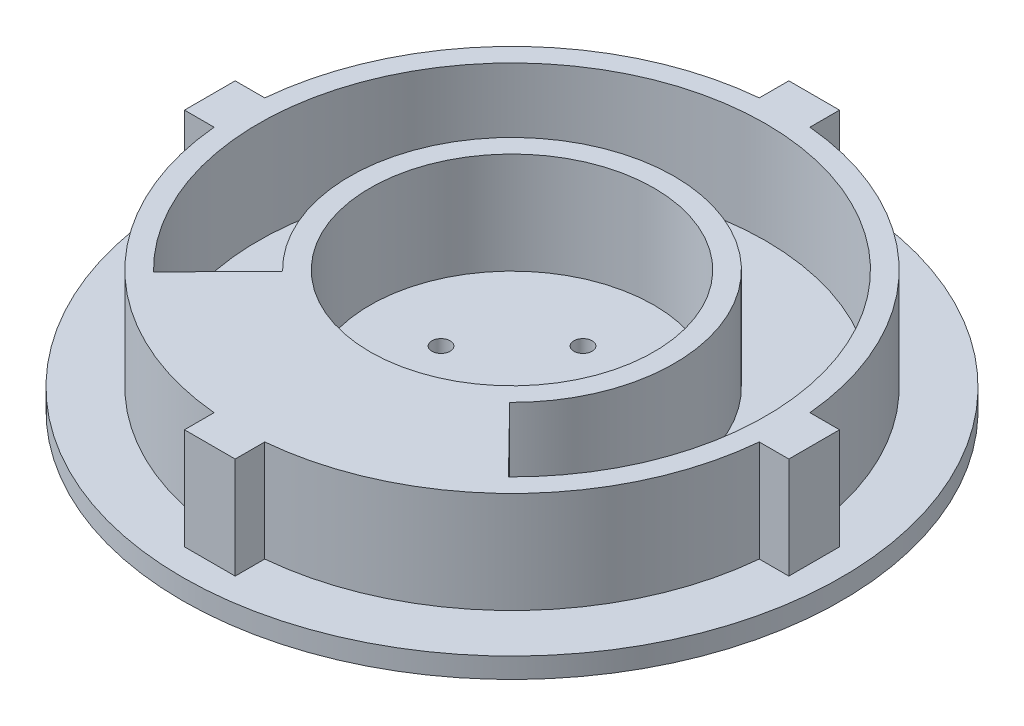
SolidWorks part; units mm, degrees
ref_plane "Front Plane" through (0, 0, 0) normal (0, 0, 1) x (1, 0, 0)
ref_plane "Top Plane" through (0, 0, 0) normal (0, 1, 0) x (1, 0, 0)
ref_plane "Right Plane" through (0, 0, 0) normal (1, 0, 0) x (0, 0, -1)
sketch "Sketch1" plane through (0, 0, 0) normal (0, 1, 0) x (1, 0, 0)
  line L0 (-17.5, -17.8536) -> (-11.2, -11.4263)
  line L1 (0, -55) -> (0, 55) construction
  line L2 (17.5, -17.8536) -> (11.2, -11.4263)
  line L4 (-17.5, -17.8536) -> (3.8221, -38.7535) construction
  circle A0 centre (0, 0) radius 27
  arc A1 (11.2, -11.4263) -> (-11.2, -11.4263) centre (0, 0) ccw
  arc A2 (17.5, -17.8536) -> (-17.5, -17.8536) centre (0, 0) ccw
  circle A3 centre (0, 0) radius 14
  arc A4 (16.5039, 11.7639) -> (14.35, -14.6399) centre (0.1913, -0.1952) cw construction
  circle A5 centre (0, 0) radius 19.9533 construction
  dimension "D1" = 54
  dimension "D2" = 2
  dimension "D3" = 9
  dimension "D4" = 2
  dimension "D5" = 35
extrude "Boss-Extrude1" add sketch "Sketch1" along normal blind 10
sketch "Sketch2" plane through (0, 0, 0) normal (0, -1, 0) x (1, 0, 0)
  circle A0 centre (0, 0) radius 32.5
  circle A1 centre (0, 0) radius 14 construction
  circle A2 centre (0, 0) radius 14 construction
  dimension "D1" = 65
extrude "Boss-Extrude2" add sketch "Sketch2" along normal blind 2
sketch "Sketch3" plane through (0, 0, 0) normal (0, 1, 0) x (1, 0, 0)
  line L0 (0, -5.5) -> (0, 5.5) construction
  line L1 (-2.5, 29.8) -> (2.5, 29.8)
  line L2 (-2.5, 29.8) -> (-2.5, 25.4032)
  line L3 (-2.5, 25.4032) -> (2.5, 25.4032)
  line L4 (2.5, 29.8) -> (2.5, 25.4032)
  line L5 (-2.5, 29.8) -> (2.5, 25.4032) construction
  line L6 (-2.5, 25.4032) -> (2.5, 29.8) construction
  line L7 (29.8, 2.5) -> (25.4032, 2.5)
  line L8 (29.8, 2.5) -> (29.8, -2.5)
  line L9 (29.8, -2.5) -> (25.4032, -2.5)
  line L10 (25.4032, 2.5) -> (25.4032, -2.5)
  line L11 (2.5, -29.8) -> (2.5, -25.4032)
  line L12 (2.5, -29.8) -> (-2.5, -29.8)
  line L13 (-2.5, -29.8) -> (-2.5, -25.4032)
  line L14 (2.5, -25.4032) -> (-2.5, -25.4032)
  line L15 (-29.8, -2.5) -> (-25.4032, -2.5)
  line L16 (-29.8, -2.5) -> (-29.8, 2.5)
  line L17 (-29.8, 2.5) -> (-25.4032, 2.5)
  line L18 (-25.4032, -2.5) -> (-25.4032, 2.5)
  circle A1 centre (0, 0) radius 27 construction
  point P0 (0, 27.6016)
  dimension "D2" = 29.8
  dimension "D1" = 5
  dimension "D3" = 4
extrude "Boss-Extrude3" add sketch "Sketch3" along normal blind 10
sketch "Sketch4" plane through (0, -2, 0) normal (0, -1, 0) x (1, 0, 0)
  circle A0 centre (0, 0) radius 7 construction
  circle A1 centre (0, -7) radius 0.9
  circle A2 centre (-7, 0) radius 0.9
  circle A3 centre (0, 7) radius 0.9
  circle A4 centre (7, 0) radius 0.9
  point P14 (0, 0)
  dimension "D1" = 14
  dimension "D2" = 1.8
  dimension "D3" = 4
extrude "Cut-Extrude1" cut sketch "Sketch4" against normal up to next
